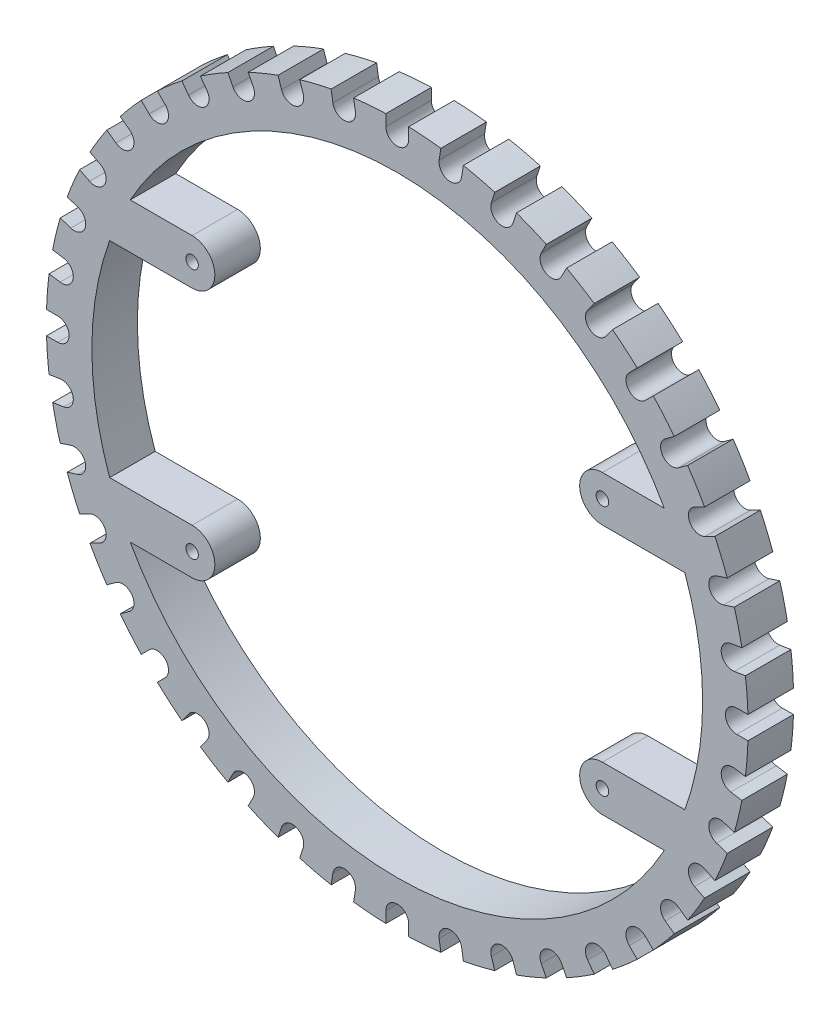
SolidWorks part; units mm, degrees
ref_plane "Front Plane" through (0, 0, 0) normal (0, 0, 1) x (1, 0, 0)
ref_plane "Top Plane" through (0, 0, 0) normal (0, 1, 0) x (1, 0, 0)
ref_plane "Right Plane" through (0, 0, 0) normal (1, 0, 0) x (0, 0, -1)
sketch "Sketch1" plane through (0, 0, 0) normal (0, 0, 1) x (1, 0, 0)
  line L0 (-57.254, -35) -> (57.254, -35) construction
  line L3 (0, 0) -> (0, -97.925) construction
  line L4 (-3.175, -94.75) -> (-3.175, -97.8735)
  line L5 (3.175, -94.75) -> (3.175, -97.8735)
  line L6 (-57.254, -28.65) -> (-80.265, -28.65)
  line L7 (-57.254, -41.35) -> (-74.5217, -41.35)
  line L8 (-11.6863, -94.0801) -> (-12.1749, -97.1652)
  line L9 (-17.9581, -93.0868) -> (-18.4467, -96.1719)
  line L10 (-26.2598, -91.0937) -> (-27.225, -94.0644)
  line L11 (-32.299, -89.1315) -> (-33.2642, -92.1021)
  line L12 (-40.1867, -85.8643) -> (-41.6047, -88.6474)
  line L13 (-45.8445, -82.9814) -> (-47.2626, -85.7645)
  line L14 (-53.124, -78.5206) -> (-54.96, -81.0476)
  line L15 (-58.2613, -74.7881) -> (-60.0972, -77.3151)
  line L16 (-64.7533, -69.2434) -> (-66.962, -71.4521)
  line L17 (-69.2434, -64.7533) -> (-71.4521, -66.962)
  line L18 (-74.7881, -58.2613) -> (-77.3151, -60.0972)
  line L19 (-78.5206, -53.124) -> (-81.0476, -54.96)
  line L20 (-82.9814, -45.8445) -> (-85.7645, -47.2626)
  line L21 (-85.8643, -40.1867) -> (-88.6474, -41.6047)
  line L22 (-89.1315, -32.299) -> (-92.1021, -33.2642)
  line L23 (-91.0937, -26.2598) -> (-94.0644, -27.225)
  line L24 (-93.0868, -17.9581) -> (-96.1719, -18.4467)
  line L25 (-94.0801, -11.6863) -> (-97.1652, -12.1749)
  line L26 (-94.75, -3.175) -> (-97.8735, -3.175)
  line L27 (-94.75, 3.175) -> (-97.8735, 3.175)
  line L28 (-94.0801, 11.6863) -> (-97.1652, 12.1749)
  line L29 (-93.0868, 17.9581) -> (-96.1719, 18.4467)
  line L30 (-91.0937, 26.2598) -> (-94.0644, 27.225)
  line L31 (-89.1315, 32.299) -> (-92.1021, 33.2642)
  line L32 (-85.8643, 40.1867) -> (-88.6474, 41.6047)
  line L33 (-82.9814, 45.8445) -> (-85.7645, 47.2626)
  line L34 (-78.5206, 53.124) -> (-81.0476, 54.96)
  line L35 (-74.7881, 58.2613) -> (-77.3151, 60.0972)
  line L36 (-69.2434, 64.7533) -> (-71.4521, 66.962)
  line L37 (-64.7533, 69.2434) -> (-66.962, 71.4521)
  line L38 (-58.2613, 74.7881) -> (-60.0972, 77.3151)
  line L39 (-53.124, 78.5206) -> (-54.96, 81.0476)
  line L40 (-45.8445, 82.9814) -> (-47.2626, 85.7645)
  line L41 (-40.1867, 85.8643) -> (-41.6047, 88.6474)
  line L42 (-32.299, 89.1315) -> (-33.2642, 92.1021)
  line L43 (-26.2598, 91.0937) -> (-27.225, 94.0644)
  line L44 (-17.9581, 93.0868) -> (-18.4467, 96.1719)
  line L45 (-11.6863, 94.0801) -> (-12.1749, 97.1652)
  line L46 (-3.175, 94.75) -> (-3.175, 97.8735)
  line L47 (3.175, 94.75) -> (3.175, 97.8735)
  line L48 (11.6863, 94.0801) -> (12.1749, 97.1652)
  line L49 (17.9581, 93.0868) -> (18.4467, 96.1719)
  line L50 (26.2598, 91.0937) -> (27.225, 94.0644)
  line L51 (32.299, 89.1315) -> (33.2642, 92.1021)
  line L52 (40.1867, 85.8643) -> (41.6047, 88.6474)
  line L53 (45.8445, 82.9814) -> (47.2626, 85.7645)
  line L54 (53.124, 78.5206) -> (54.96, 81.0476)
  line L55 (58.2613, 74.7881) -> (60.0972, 77.3151)
  line L56 (64.7533, 69.2434) -> (66.962, 71.4521)
  line L57 (69.2434, 64.7533) -> (71.4521, 66.962)
  line L58 (74.7881, 58.2613) -> (77.3151, 60.0972)
  line L59 (78.5206, 53.124) -> (81.0476, 54.96)
  line L60 (82.9814, 45.8445) -> (85.7645, 47.2626)
  line L61 (85.8643, 40.1867) -> (88.6474, 41.6047)
  line L62 (89.1315, 32.299) -> (92.1021, 33.2642)
  line L63 (91.0937, 26.2598) -> (94.0644, 27.225)
  line L64 (93.0868, 17.9581) -> (96.1719, 18.4467)
  line L65 (94.0801, 11.6863) -> (97.1652, 12.1749)
  line L66 (94.75, 3.175) -> (97.8735, 3.175)
  line L67 (94.75, -3.175) -> (97.8735, -3.175)
  line L68 (94.0801, -11.6863) -> (97.1652, -12.1749)
  line L69 (93.0868, -17.9581) -> (96.1719, -18.4467)
  line L70 (91.0937, -26.2598) -> (94.0644, -27.225)
  line L71 (89.1315, -32.299) -> (92.1021, -33.2642)
  line L72 (85.8643, -40.1867) -> (88.6474, -41.6047)
  line L73 (82.9814, -45.8445) -> (85.7645, -47.2626)
  line L74 (78.5206, -53.124) -> (81.0476, -54.96)
  line L75 (74.7881, -58.2613) -> (77.3151, -60.0972)
  line L76 (69.2434, -64.7533) -> (71.4521, -66.962)
  line L77 (64.7533, -69.2434) -> (66.962, -71.4521)
  line L78 (58.2613, -74.7881) -> (60.0972, -77.3151)
  line L79 (53.124, -78.5206) -> (54.96, -81.0476)
  line L80 (45.8445, -82.9814) -> (47.2626, -85.7645)
  line L81 (40.1867, -85.8643) -> (41.6047, -88.6474)
  line L82 (32.299, -89.1315) -> (33.2642, -92.1021)
  line L83 (26.2598, -91.0937) -> (27.225, -94.0644)
  line L84 (17.9581, -93.0868) -> (18.4467, -96.1719)
  line L85 (11.6863, -94.0801) -> (12.1749, -97.1652)
  line L86 (57.254, -41.35) -> (74.5217, -41.35)
  line L87 (57.254, -28.65) -> (80.265, -28.65)
  line L88 (-85.225, 0) -> (85.225, 0) construction
  line L89 (57.254, 28.65) -> (80.265, 28.65)
  line L90 (57.254, 41.35) -> (74.5217, 41.35)
  line L91 (-57.254, 28.65) -> (-80.265, 28.65)
  line L92 (-57.254, 41.35) -> (-74.5217, 41.35)
  circle A0 centre (0, 0) radius 98.425 construction
  circle A1 centre (0, 0) radius 97.925
  circle A44 centre (0, -94.75) radius 3.175
  circle A45 centre (-14.8222, -93.5835) radius 3.175
  circle A46 centre (-29.2794, -90.1126) radius 3.175
  circle A47 centre (-43.0156, -84.4229) radius 3.175
  circle A48 centre (-55.6927, -76.6544) radius 3.175
  circle A49 centre (-66.9984, -66.9984) radius 3.175
  circle A50 centre (-76.6544, -55.6927) radius 3.175
  circle A51 centre (-84.4229, -43.0156) radius 3.175
  circle A52 centre (-90.1126, -29.2794) radius 3.175
  circle A53 centre (-93.5835, -14.8222) radius 3.175
  circle A54 centre (-94.75, 0) radius 3.175
  circle A55 centre (-93.5835, 14.8222) radius 3.175
  circle A56 centre (-90.1126, 29.2794) radius 3.175
  circle A57 centre (-84.4229, 43.0156) radius 3.175
  circle A58 centre (-76.6544, 55.6927) radius 3.175
  circle A59 centre (-66.9984, 66.9984) radius 3.175
  circle A60 centre (-55.6927, 76.6544) radius 3.175
  circle A61 centre (-43.0156, 84.4229) radius 3.175
  circle A62 centre (-29.2794, 90.1126) radius 3.175
  circle A63 centre (-14.8222, 93.5835) radius 3.175
  circle A64 centre (0, 94.75) radius 3.175
  circle A65 centre (14.8222, 93.5835) radius 3.175
  circle A66 centre (29.2794, 90.1126) radius 3.175
  circle A67 centre (43.0156, 84.4229) radius 3.175
  circle A68 centre (55.6927, 76.6544) radius 3.175
  circle A69 centre (66.9984, 66.9984) radius 3.175
  circle A70 centre (76.6544, 55.6927) radius 3.175
  circle A71 centre (84.4229, 43.0156) radius 3.175
  circle A72 centre (90.1126, 29.2794) radius 3.175
  circle A73 centre (93.5835, 14.8222) radius 3.175
  circle A74 centre (94.75, 0) radius 3.175
  circle A75 centre (93.5835, -14.8222) radius 3.175
  circle A76 centre (90.1126, -29.2794) radius 3.175
  circle A77 centre (84.4229, -43.0156) radius 3.175
  circle A78 centre (76.6544, -55.6927) radius 3.175
  circle A79 centre (66.9984, -66.9984) radius 3.175
  circle A80 centre (55.6927, -76.6544) radius 3.175
  circle A81 centre (43.0156, -84.4229) radius 3.175
  circle A82 centre (29.2794, -90.1126) radius 3.175
  circle A83 centre (14.8222, -93.5835) radius 3.175
  arc A84 (-74.5217, -41.35) -> (74.5217, -41.35) centre (0, 0) ccw
  circle A85 centre (-57.254, -35) radius 1.75
  arc A87 (-57.254, -41.35) -> (-57.254, -28.65) centre (-57.254, -35) ccw
  arc A88 (-74.5217, -41.35) -> (74.5217, -41.35) centre (0, 0) ccw
  circle A89 centre (57.254, -35) radius 1.75
  arc A90 (57.254, -41.35) -> (57.254, -28.65) centre (57.254, -35) cw
  arc A91 (80.265, -28.65) -> (80.265, 28.65) centre (0, 0) ccw
  arc A92 (80.265, -28.65) -> (80.265, 28.65) centre (0, 0) ccw
  circle A93 centre (57.254, 35) radius 1.75
  arc A94 (57.254, 41.35) -> (57.254, 28.65) centre (57.254, 35) ccw
  circle A95 centre (-57.254, 35) radius 1.75
  arc A96 (-57.254, 41.35) -> (-57.254, 28.65) centre (-57.254, 35) cw
  arc A97 (-80.265, 28.65) -> (-80.265, -28.65) centre (0, 0) ccw
  arc A98 (-80.265, 28.65) -> (-80.265, -28.65) centre (0, 0) ccw
  arc A99 (74.5217, 41.35) -> (-74.5217, 41.35) centre (0, 0) ccw
  arc A100 (74.5217, 41.35) -> (-74.5217, 41.35) centre (0, 0) ccw
  point P4 (0, -35)
  point P259 (0, 0)
  dimension "D1" = 196.85
  dimension "D2" = 0.5
  dimension "D3" = 12.7
  dimension "D5" = 40
  dimension "D6" = 6.35
  dimension "D4" = 3.5
  dimension "D8" = 114.508
  dimension "D9" = 12.7
  dimension "D7" = 35
extrude "Boss-Extrude1" add sketch "Sketch1" along normal blind 12.7
